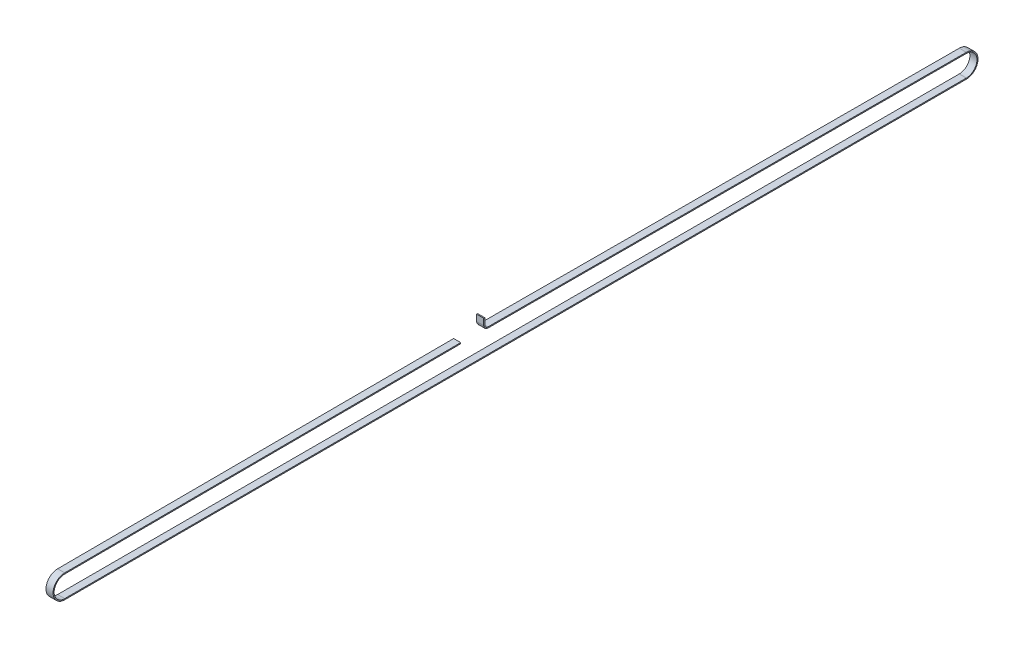
SolidWorks part; units mm, degrees
ref_plane "Front Plane" through (0, 0, 0) normal (0, 0, 1) x (1, 0, 0)
ref_plane "Top Plane" through (0, 0, 0) normal (0, 1, 0) x (1, 0, 0)
ref_plane "Right Plane" through (0, 0, 0) normal (1, 0, 0) x (0, 0, -1)
sketch "Sketch1" plane through (0, 0, 0) normal (1, 0, 0) x (0, 0, -1)
  line L0 (-637.5, 0) -> (637.5, 0) construction
  line L1 (-637.5, -15) -> (637.5, -15)
  line L2 (-637.5536, 14.9999) -> (-77.5032, 17)
  line L3 (-71.5246, 23) -> (-71.5246, 32) construction
  line L4 (637.5443, 14.9999) -> (-39.021, 17)
  line L5 (-45.0032, 23) -> (-45.0032, 32)
  line L6 (-45.0032, 32) -> (-71.5246, 32) construction
  line L7 (-77.5032, 17) -> (-39.021, 17) construction
  line L8 (-58.2639, 32) -> (-58.2621, 17) construction
  arc A0 (-637.5536, 14.9999) -> (-637.5, -15) centre (-637.5, 0) ccw
  arc A1 (637.5, -15) -> (637.5443, 14.9999) centre (637.5, 0) ccw
  arc A2 (-39.021, 17) -> (-45.0032, 23) centre (-39.0032, 23) cw
  arc A3 (-77.5032, 17) -> (-71.5246, 23) centre (-77.5246, 23) ccw construction
  dimension "D1" = 30
  dimension "D4" = 6
  dimension "D5" = 38
  dimension "D2" = 1275
  dimension "D3" = 32.5
  dimension "D6" = 15
  dimension "D7" = 579.24
extrude "Extrude-Thin1" add sketch "Sketch1" along normal mid plane 10 thin
